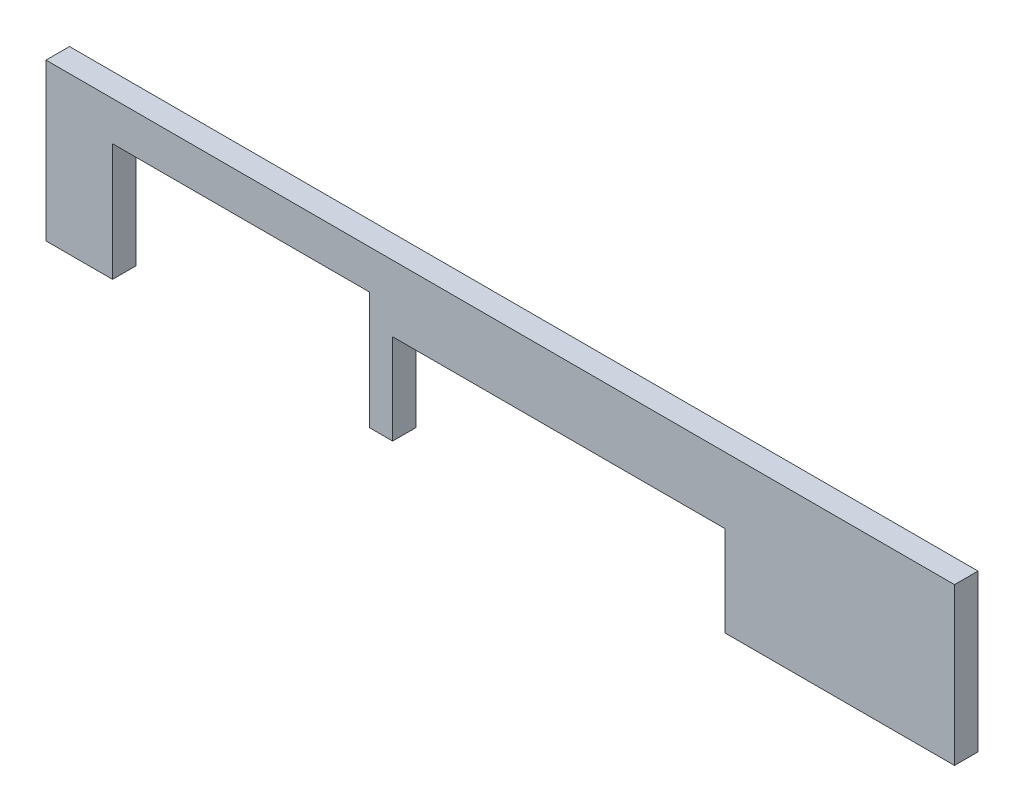
SolidWorks part; units mm, degrees
ref_plane "Front Plane" through (0, 0, 0) normal (0, 0, 1) x (1, 0, 0)
ref_plane "Top Plane" through (0, 0, 0) normal (0, 1, 0) x (1, 0, 0)
ref_plane "Right Plane" through (0, 0, 0) normal (1, 0, 0) x (0, 0, -1)
sketch "Sketch1" plane through (0, 0, 0) normal (0, 0, 1) x (1, 0, 0)
  line L0 (0, 0) -> (8.5, 0)
  line L2 (0, 0) -> (0, 20)
  line L3 (0, 20) -> (116, 20)
  line L4 (116, 0) -> (116, 20)
  line L5 (8.5, 0) -> (8.5, 15)
  line L6 (8.5, 15) -> (41.3362, 15)
  line L7 (41.3362, 15) -> (41.3362, 0)
  line L8 (41.3362, 0) -> (44.2589, 0)
  line L9 (44.2589, 0) -> (44.2589, 11.5366)
  line L10 (44.2589, 11.5366) -> (86.674, 11.5366)
  line L11 (86.674, 11.5366) -> (86.674, 0)
  line L12 (86.674, 0) -> (116, 0)
  point P5 (0, 0)
  point P14 (0, 0)
  point P15 (0, 0)
  point P16 (0, 0)
  point P17 (0, 0)
  dimension "D1" = 116
extrude "Boss-Extrude1" add sketch "Sketch1" along normal blind 3
